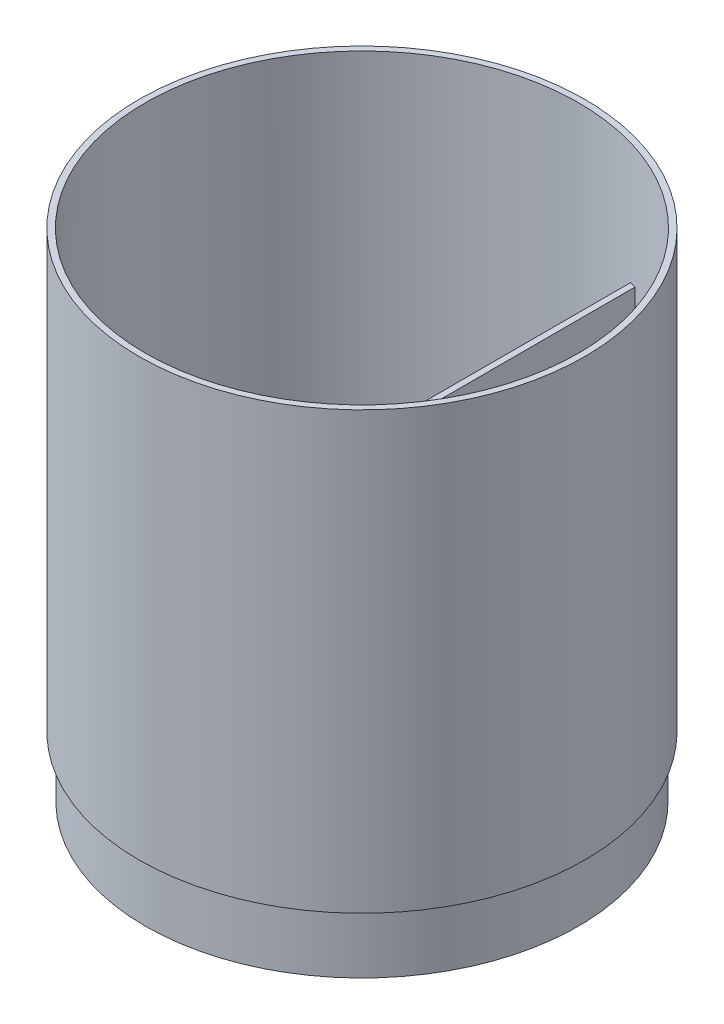
SolidWorks part; units mm, degrees
ref_plane "Front Plane" through (0, 0, 0) normal (0, 0, 1) x (1, 0, 0)
ref_plane "Top Plane" through (0, 0, 0) normal (0, 1, 0) x (1, 0, 0)
ref_plane "Right Plane" through (0, 0, 0) normal (1, 0, 0) x (0, 0, -1)
sketch "Sketch1" plane through (0, 0, 0) normal (0, 1, 0) x (1, 0, 0)
  circle A0 centre (0, 0) radius 35.75
  circle A1 centre (0, 0) radius 34.75
  dimension "D1" = 71.5
  dimension "D2" = 1
extrude "Boss-Extrude1" add sketch "Sketch1" along normal blind 10
sketch "Sketch2" plane through (0, 10, 0) normal (0, 1, 0) x (1, 0, 0)
  circle A3 centre (0, 0) radius 34.75 construction
  circle A4 centre (0, 0) radius 34.75
  circle A9 centre (0, 0) radius 36.8
  dimension "D1" = 73.6
extrude "Boss-Extrude3" add sketch "Sketch2" along normal blind 2
sketch "Sketch3" plane through (0, 12, 0) normal (0, 1, 0) x (1, 0, 0)
  circle A0 centre (0, 0) radius 36.8 construction
  circle A1 centre (0, 0) radius 36.8
  circle A2 centre (0, 0) radius 35.8
  dimension "D1" = 1
extrude "Boss-Extrude4" add sketch "Sketch3" along normal blind 70
sketch "Sketch4" plane through (0, 12, 0) normal (0, 1, 0) x (1, 0, 0)
  line L0 (10, 34.375) -> (10, -34.375)
  line L1 (11, 34.375) -> (11, -34.375)
  line L2 (10, 34.375) -> (11, 34.375)
  line L3 (10, -34.375) -> (11, -34.375)
  circle A0 centre (0, 0) radius 35.8 construction
  circle A1 centre (0, 0) radius 35.8 construction
  dimension "D1" = 10
  dimension "D2" = 1
extrude "Boss-Extrude5" add sketch "Sketch4" along normal blind 50
ref_plane "Plane1" through (-36.8, 0, 0) normal (-1, 0, 0) x (0, 0, 1)
sketch "Sketch5" plane through (-36.8, 0, 0) normal (-1, 0, 0) x (0, 0, 1)
  line L0 (0, 0) -> (0, 35.1075) construction
  circle A0 centre (0, 20) radius 7.5
  dimension "D1" = 15
  dimension "D2" = 20
extrude "Cut-Extrude1" cut sketch "Sketch5" against normal blind 10
